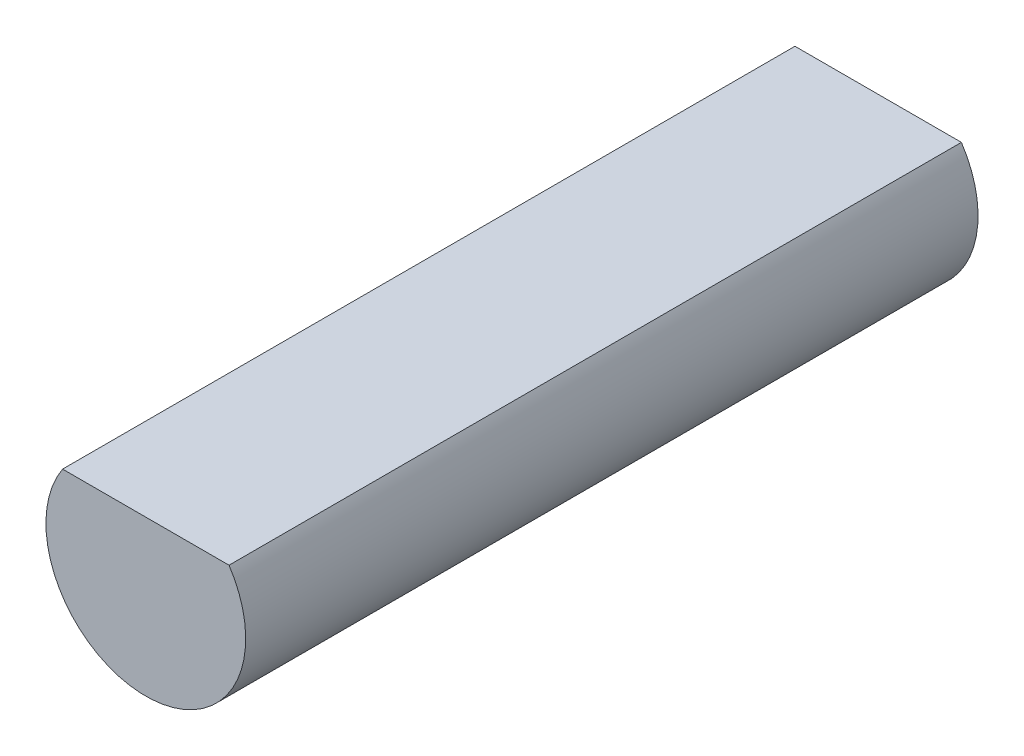
SolidWorks part; units mm, degrees
material "镀铬不锈钢"
ref_plane "前视基准面" through (0, 0, 0) normal (0, 0, 1) x (1, 0, 0)
ref_plane "上视基准面" through (0, 0, 0) normal (0, 1, 0) x (1, 0, 0)
ref_plane "右视基准面" through (0, 0, 0) normal (1, 0, 0) x (0, 0, -1)
sketch "草图1" plane through (0, 0, 0) normal (0, 0, 1) x (1, 0, 0)
  line L0 (-2.5, 1.6583) -> (2.5, 1.6583)
  circle A0 centre (0, 0) radius 3
  dimension "D1" = 6
  dimension "D2" = 5
extrude "凸台-拉伸1" add sketch "草图1" along normal blind 22 contours L0 A0
